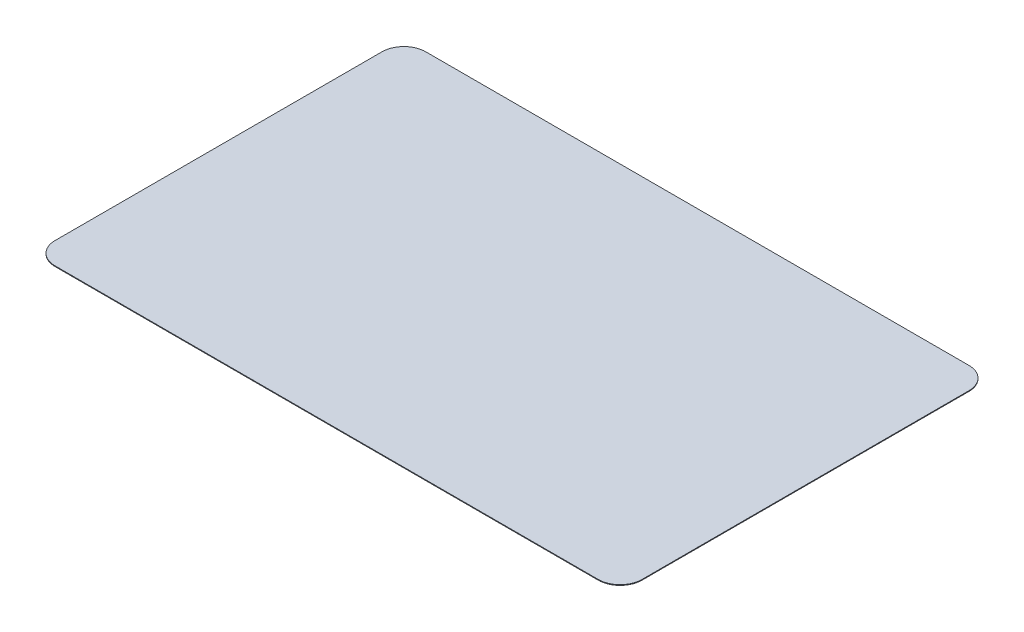
SolidWorks part; units mm, degrees
ref_plane "前视基准面" through (0, 0, 0) normal (0, 0, 1) x (1, 0, 0)
ref_plane "上视基准面" through (0, 0, 0) normal (0, 1, 0) x (1, 0, 0)
ref_plane "右视基准面" through (0, 0, 0) normal (1, 0, 0) x (0, 0, -1)
sketch "草图1" plane through (0, 0, 0) normal (0, 1, 0) x (1, 0, 0)
  line L1 (-39.57, -27) -> (39.57, -27)
  line L2 (-42.75, -23.82) -> (-42.75, 23.82)
  line L3 (-39.57, 27) -> (39.57, 27)
  line L4 (42.75, -23.82) -> (42.75, 23.82)
  line L5 (-42.75, -27) -> (42.75, 27) construction
  line L6 (-42.75, 27) -> (42.75, -27) construction
  arc A0 (-42.75, 23.82) -> (-39.57, 27) centre (-39.57, 23.82) cw
  arc A1 (39.57, -27) -> (42.75, -23.82) centre (39.57, -23.82) ccw
  arc A2 (-39.57, -27) -> (-42.75, -23.82) centre (-39.57, -23.82) cw
  arc A3 (39.57, 27) -> (42.75, 23.82) centre (39.57, 23.82) cw
  point P0 (0, 0)
  dimension "D3" = 3.18
  dimension "D1" = 85.5
  dimension "D2" = 54
extrude "凸台-拉伸1" add sketch "草图1" along normal blind 0.1
